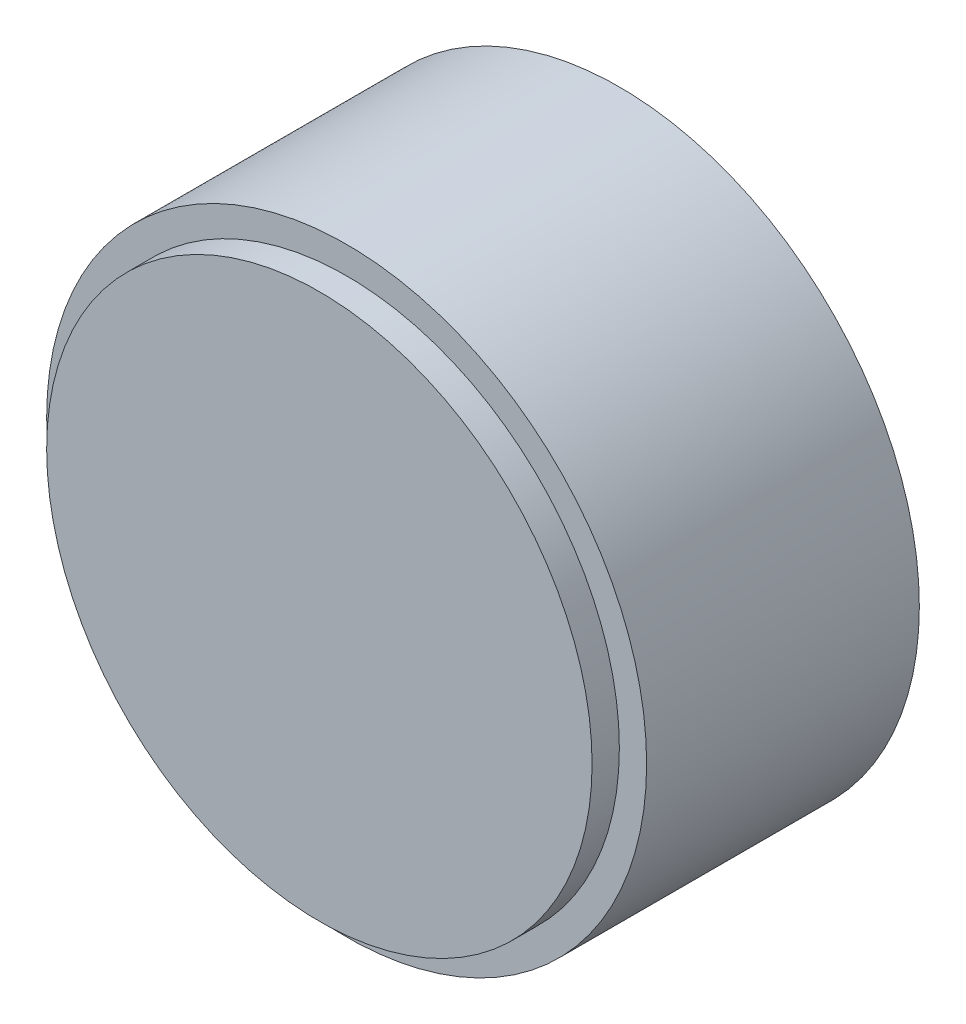
SolidWorks part; units mm, degrees
ref_plane "Plan de face" through (0, 0, 0) normal (0, 0, 1) x (1, 0, 0)
ref_plane "Plan de dessus" through (0, 0, 0) normal (0, 1, 0) x (1, 0, 0)
ref_plane "Plan de droite" through (0, 0, 0) normal (1, 0, 0) x (0, 0, -1)
sketch "Esquisse1" plane through (0, 0, 0) normal (0, 0, 1) x (1, 0, 0)
  circle A0 centre (0, 0) radius 30
  point P14 (0, 0)
  dimension "D1" = 60
extrude "Boss.-Extru.1" add sketch "Esquisse1" along normal blind 35
sketch "Esquisse3" plane through (0, 0, 0) normal (0, 0, -1) x (-1, 0, 0)
  circle A2 centre (0, 0) radius 30 construction
  circle A3 centre (0, 0) radius 33
  circle A4 centre (0, 0) radius 33
  circle A5 centre (0, 0) radius 30
  dimension "D1" = 3
extrude "Boss.-Extru.2" add sketch "Esquisse3" against normal blind 30 from offset 2 offset against normal yes
sketch "Esquisse4" plane through (0, 0, 0) normal (0, 0, -1) x (-1, 0, 0)
  circle A0 centre (0, 0) radius 2
  circle A2 centre (0, 0) radius 7
  dimension "D1" = 4
  dimension "D2" = 5
extrude "Boss.-Extru.3" add sketch "Esquisse4" along normal blind 5
sketch "Esquisse5" plane through (0, 0, 0) normal (0, 1, 0) x (1, 0, 0)
  line L0 (2, 5) -> (-2, 5) construction
  line L1 (2, 5) -> (-2, 5)
  line L2 (30, 0) -> (-30, 0) construction
  line L3 (30, 0) -> (-30, 0)
  line L4 (-7, 5) -> (-7, 0) construction
  line L5 (-7, 5) -> (-7, 0)
  circle A0 centre (0, 2.5) radius 1.5
  point P10 (-7, 2.5)
  dimension "D1" = 3
extrude "Enlèv. mat.-Extru.1" cut sketch "Esquisse5" along normal through all contours A0
